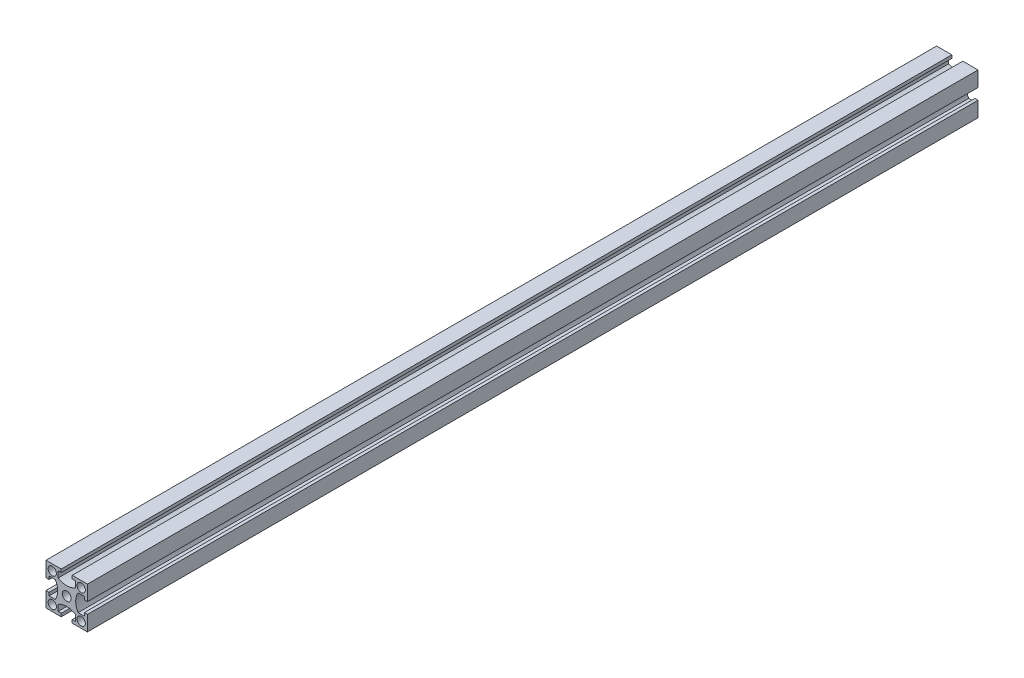
SolidWorks part; units mm, degrees
material "6061-T6 (SS)"
ref_plane "정면" through (0, 0, 0) normal (0, 0, 1) x (1, 0, 0)
ref_plane "윗면" through (0, 0, 0) normal (0, 1, 0) x (1, 0, 0)
ref_plane "우측면" through (0, 0, 0) normal (1, 0, 0) x (0, 0, -1)
sketch "스케치1" plane through (0, 0, 0) normal (0, 0, 1) x (1, 0, 0)
  line L1 (-10, 10) -> (10, 10)
  line L2 (-10, 10) -> (-10, -10)
  line L3 (-10, -10) -> (10, -10)
  line L4 (10, 10) -> (10, -10)
  line L5 (-10, 10) -> (10, -10) construction
  line L6 (-10, -10) -> (10, 10) construction
  point P0 (0, 0)
  dimension "D1" = 20
  dimension "D2" = 20
extrude "보스-돌출1" add sketch "스케치1" along normal blind 430
sketch "스케치2" plane through (0, 0, 430) normal (0, 0, 1) x (1, 0, 0)
  line L0 (-2.65, 10) -> (-2.65, 8.5)
  line L1 (10, 10) -> (-10, 10) construction
  line L2 (-2.65, 8.5) -> (-4.15, 8.5)
  line L3 (-4.15, 8.5) -> (-4.15, 5.5)
  line L4 (-2.65, 10) -> (2.65, 10)
  line L5 (2.65, 10) -> (2.65, 8.5)
  line L6 (2.65, 8.5) -> (4.15, 8.5)
  line L7 (4.15, 8.5) -> (4.15, 5.5)
  line L8 (10, 2.65) -> (8.5, 2.65)
  line L9 (8.5, 2.65) -> (8.5, 4.15)
  line L10 (8.5, 4.15) -> (5.5, 4.15)
  line L11 (10, 2.65) -> (10, -2.65)
  line L12 (10, -2.65) -> (8.5, -2.65)
  line L13 (8.5, -2.65) -> (8.5, -4.15)
  line L14 (8.5, -4.15) -> (5.5, -4.15)
  line L15 (2.65, -10) -> (2.65, -8.5)
  line L16 (2.65, -8.5) -> (4.15, -8.5)
  line L17 (4.15, -8.5) -> (4.15, -5.5)
  line L18 (2.65, -10) -> (-2.65, -10)
  line L19 (-2.65, -10) -> (-2.65, -8.5)
  line L20 (-2.65, -8.5) -> (-4.15, -8.5)
  line L21 (-4.15, -8.5) -> (-4.15, -5.5)
  line L22 (-10, -2.65) -> (-8.5, -2.65)
  line L23 (-8.5, -2.65) -> (-8.5, -4.15)
  line L24 (-8.5, -4.15) -> (-5.5, -4.15)
  line L25 (-10, -2.65) -> (-10, 2.65)
  line L26 (-10, 2.65) -> (-8.5, 2.65)
  line L27 (-8.5, 2.65) -> (-8.5, 4.15)
  line L28 (-8.5, 4.15) -> (-5.5, 4.15)
  arc A1 (-4.15, 5.5) -> (4.15, 5.5) centre (0, 12.3394) ccw
  arc A2 (5.5, 4.15) -> (5.5, -4.15) centre (12.3394, 0) ccw
  arc A3 (4.15, -5.5) -> (-4.15, -5.5) centre (0, -12.3394) ccw
  arc A4 (-5.5, -4.15) -> (-5.5, 4.15) centre (-12.3394, 0) ccw
  circle A5 centre (0, 0) radius 2.15
  circle A6 centre (-7, 7) radius 2
  circle A7 centre (7, 7) radius 2
  circle A8 centre (7, -7) radius 2
  circle A9 centre (-7, -7) radius 2
  point P4 (-2.65, 9.25)
  point P43 (0, 0)
  dimension "D2" = 1.5
  dimension "D8" = 4.3
  dimension "D9" = 4
  dimension "D10" = 4
  dimension "D11" = 4
  dimension "D12" = 4
  dimension "D21" = 8
  dimension "D1" = 5.3
  dimension "D3" = 8.3
  dimension "D4" = 4.15
  dimension "D5" = 2.65
  dimension "D6" = 4
  dimension "D7" = 3
  dimension "D13" = 14
  dimension "D14" = 7
  dimension "D15" = 7
  dimension "D16" = 7
  dimension "D17" = 14
  dimension "D18" = 7
  dimension "D19" = 7
  dimension "D20" = 7
extrude "컷-돌출1" cut sketch "스케치2" against normal through all
